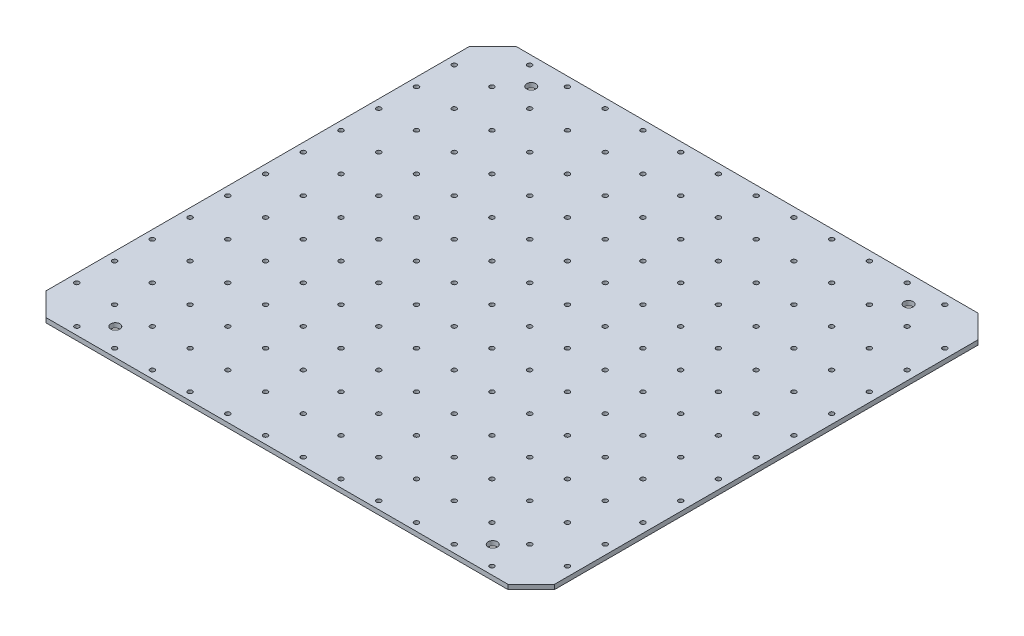
SolidWorks part; units mm, degrees
ref_plane "Front Plane" through (0, 0, 0) normal (0, 0, 1) x (1, 0, 0)
ref_plane "Top Plane" through (0, 0, 0) normal (0, 1, 0) x (1, 0, 0)
ref_plane "Right Plane" through (0, 0, 0) normal (1, 0, 0) x (0, 0, -1)
sketch "Sketch3" plane through (0, 0, 0) normal (0, 1, 0) x (1, 0, 0)
  line L0 (-289.1077, -12.0015) -> (-289.1077, 262.9985)
  line L1 (-289.1077, 262.9985) -> (-274.1077, 277.9985)
  line L2 (-274.1077, 277.9985) -> (25.8923, 277.9985)
  line L3 (25.8923, 277.9985) -> (40.8923, 262.9985)
  line L4 (40.8923, 262.9985) -> (40.8923, -12.0015)
  line L5 (40.8923, -12.0015) -> (25.8923, -27.0015)
  line L6 (25.8923, -27.0015) -> (-274.1077, -27.0015)
  line L7 (-274.1077, -27.0015) -> (-289.1077, -12.0015)
  line L8 (-274.1077, -31.4199) -> (-274.1077, 49968.5801) construction
  line L9 (25.8923, -27.0605) -> (25.8923, 49972.9395) construction
  line L10 (-289.1667, 262.9985) -> (49710.8333, 262.9985) construction
  dimension "D1" = 300
  dimension "D2" = 275
  dimension "D3" = 300
  dimension "D4" = 275
  dimension "D5" = 15
  dimension "D6" = 15
  dimension "D7" = 15
  dimension "D8" = 15
  dimension "D9" = 15
extrude "Boss-Extrude1" add sketch "Sketch3" along normal blind 3
hole_wizard "Ø3.0mm Dowel Slot3" positions "Sketch8" profile "Sketch9" size "Ø3.0" standard "ANSI Metric" slot yes
sketch "Sketch8" plane through (0, 3, 0) normal (0, 1, 0) x (1, 0, 0)
  line L0 (-274.1077, -27.0015) -> (25.8923, -27.0015) construction
  line L1 (-289.1077, 262.9985) -> (-289.1077, -12.0015) construction
  point P0 (-259.1077, -22.0015)
  point P11 (-234.6077, -22.0015)
  point P12 (-210.1077, -22.0015)
  point P13 (-185.6077, -22.0015)
  point P14 (-161.1077, -22.0015)
  point P15 (-136.6077, -22.0015)
  point P16 (-112.1077, -22.0015)
  point P17 (-87.6077, -22.0015)
  point P18 (-63.1077, -22.0015)
  point P19 (-38.6077, -22.0015)
  point P20 (-14.1077, -22.0015)
  point P21 (10.3923, -22.0015)
  point P30 (-259.1077, 2.4985)
  point P31 (-259.1077, 26.9985)
  point P32 (-259.1077, 51.4985)
  point P33 (-259.1077, 75.9985)
  point P34 (-259.1077, 100.4985)
  point P35 (-259.1077, 124.9985)
  point P36 (-259.1077, 149.4985)
  point P37 (-259.1077, 173.9985)
  point P38 (-259.1077, 198.4985)
  point P39 (-259.1077, 222.9985)
  point P40 (-259.1077, 247.4985)
  point P41 (-259.1077, 271.9985)
  point P60 (-234.6077, 2.4985)
  point P61 (-210.1077, 2.4985)
  point P62 (-185.6077, 2.4985)
  point P63 (-161.1077, 2.4985)
  point P64 (-136.6077, 2.4985)
  point P65 (-112.1077, 2.4985)
  point P66 (-87.6077, 2.4985)
  point P67 (-63.1077, 2.4985)
  point P68 (-38.6077, 2.4985)
  point P69 (-14.1077, 2.4985)
  point P70 (10.3923, 2.4985)
  point P71 (-234.6077, 26.9985)
  point P72 (-210.1077, 26.9985)
  point P73 (-185.6077, 26.9985)
  point P74 (-161.1077, 26.9985)
  point P75 (-136.6077, 26.9985)
  point P76 (-112.1077, 26.9985)
  point P77 (-87.6077, 26.9985)
  point P78 (-63.1077, 26.9985)
  point P79 (-38.6077, 26.9985)
  point P80 (-14.1077, 26.9985)
  point P81 (10.3923, 26.9985)
  point P82 (-234.6077, 51.4985)
  point P83 (-210.1077, 51.4985)
  point P84 (-185.6077, 51.4985)
  point P85 (-161.1077, 51.4985)
  point P86 (-136.6077, 51.4985)
  point P87 (-112.1077, 51.4985)
  point P88 (-87.6077, 51.4985)
  point P89 (-63.1077, 51.4985)
  point P90 (-38.6077, 51.4985)
  point P91 (-14.1077, 51.4985)
  point P92 (10.3923, 51.4985)
  point P93 (-234.6077, 75.9985)
  point P94 (-210.1077, 75.9985)
  point P95 (-185.6077, 75.9985)
  point P96 (-161.1077, 75.9985)
  point P97 (-136.6077, 75.9985)
  point P98 (-112.1077, 75.9985)
  point P99 (-87.6077, 75.9985)
  point P100 (-63.1077, 75.9985)
  point P101 (-38.6077, 75.9985)
  point P102 (-14.1077, 75.9985)
  point P103 (10.3923, 75.9985)
  point P104 (-234.6077, 100.4985)
  point P105 (-210.1077, 100.4985)
  point P106 (-185.6077, 100.4985)
  point P107 (-161.1077, 100.4985)
  point P108 (-136.6077, 100.4985)
  point P109 (-112.1077, 100.4985)
  point P110 (-87.6077, 100.4985)
  point P111 (-63.1077, 100.4985)
  point P112 (-38.6077, 100.4985)
  point P113 (-14.1077, 100.4985)
  point P114 (10.3923, 100.4985)
  point P115 (-234.6077, 124.9985)
  point P116 (-210.1077, 124.9985)
  point P117 (-185.6077, 124.9985)
  point P118 (-161.1077, 124.9985)
  point P119 (-136.6077, 124.9985)
  point P120 (-112.1077, 124.9985)
  point P121 (-87.6077, 124.9985)
  point P122 (-63.1077, 124.9985)
  point P123 (-38.6077, 124.9985)
  point P124 (-14.1077, 124.9985)
  point P125 (10.3923, 124.9985)
  point P126 (-234.6077, 149.4985)
  point P127 (-210.1077, 149.4985)
  point P128 (-185.6077, 149.4985)
  point P129 (-161.1077, 149.4985)
  point P130 (-136.6077, 149.4985)
  point P131 (-112.1077, 149.4985)
  point P132 (-87.6077, 149.4985)
  point P133 (-63.1077, 149.4985)
  point P134 (-38.6077, 149.4985)
  point P135 (-14.1077, 149.4985)
  point P136 (10.3923, 149.4985)
  point P137 (-234.6077, 173.9985)
  point P138 (-210.1077, 173.9985)
  point P139 (-185.6077, 173.9985)
  point P140 (-161.1077, 173.9985)
  point P141 (-136.6077, 173.9985)
  point P142 (-112.1077, 173.9985)
  point P143 (-87.6077, 173.9985)
  point P144 (-63.1077, 173.9985)
  point P145 (-38.6077, 173.9985)
  point P146 (-14.1077, 173.9985)
  point P147 (10.3923, 173.9985)
  point P148 (-234.6077, 198.4985)
  point P149 (-210.1077, 198.4985)
  point P150 (-185.6077, 198.4985)
  point P151 (-161.1077, 198.4985)
  point P152 (-136.6077, 198.4985)
  point P153 (-112.1077, 198.4985)
  point P154 (-87.6077, 198.4985)
  point P155 (-63.1077, 198.4985)
  point P156 (-38.6077, 198.4985)
  point P157 (-14.1077, 198.4985)
  point P158 (10.3923, 198.4985)
  point P159 (-234.6077, 222.9985)
  point P160 (-210.1077, 222.9985)
  point P161 (-185.6077, 222.9985)
  point P162 (-161.1077, 222.9985)
  point P163 (-136.6077, 222.9985)
  point P164 (-112.1077, 222.9985)
  point P165 (-87.6077, 222.9985)
  point P166 (-63.1077, 222.9985)
  point P167 (-38.6077, 222.9985)
  point P168 (-14.1077, 222.9985)
  point P169 (10.3923, 222.9985)
  point P170 (-234.6077, 247.4985)
  point P171 (-210.1077, 247.4985)
  point P172 (-185.6077, 247.4985)
  point P173 (-161.1077, 247.4985)
  point P174 (-136.6077, 247.4985)
  point P175 (-112.1077, 247.4985)
  point P176 (-87.6077, 247.4985)
  point P177 (-63.1077, 247.4985)
  point P178 (-38.6077, 247.4985)
  point P179 (-14.1077, 247.4985)
  point P180 (10.3923, 247.4985)
  point P181 (-234.6077, 271.9985)
  point P182 (-210.1077, 271.9985)
  point P183 (-185.6077, 271.9985)
  point P184 (-161.1077, 271.9985)
  point P185 (-136.6077, 271.9985)
  point P186 (-112.1077, 271.9985)
  point P187 (-87.6077, 271.9985)
  point P188 (-63.1077, 271.9985)
  point P189 (-38.6077, 271.9985)
  point P190 (-14.1077, 271.9985)
  point P191 (10.3923, 271.9985)
  point P224 (34.8923, 2.4985)
  point P225 (34.8923, 26.9985)
  point P226 (34.8923, 51.4985)
  point P227 (34.8923, 75.9985)
  point P228 (34.8923, 100.4985)
  point P229 (34.8923, 124.9985)
  point P230 (34.8923, 149.4985)
  point P231 (34.8923, 173.9985)
  point P232 (34.8923, 198.4985)
  point P233 (34.8923, 222.9985)
  point P234 (34.8923, 247.4985)
  point P254 (-283.6077, 2.4985)
  point P255 (-283.6077, 26.9985)
  point P256 (-283.6077, 51.4985)
  point P257 (-283.6077, 75.9985)
  point P258 (-283.6077, 100.4985)
  point P259 (-283.6077, 124.9985)
  point P260 (-283.6077, 149.4985)
  point P261 (-283.6077, 173.9985)
  point P262 (-283.6077, 198.4985)
  point P263 (-283.6077, 222.9985)
  point P264 (-283.6077, 247.4985)
  dimension "D1" = 5
  dimension "D2" = 30
  dimension "D6" = 2
  dimension "D3" = 12
  dimension "D4" = 13
  dimension "D5" = 13
  dimension "D7" = 2
sketch "Sketch9" plane through (-259.1077, 3, 22.0015) normal (1, 0, 0) x (0, 0, 1)
  line L0 (0, 0) -> (0, 6.1013)
  line L1 (0, 6.1013) -> (1.5, 5.2)
  line L2 (1.5, 5.2) -> (1.5, 0)
  line L5 (1.5, 0) -> (0, 0)
  line L10 (0, 6.1013) -> (-1.5, 5.2) construction
  line L11 (0, -6.35) -> (0, 107.95) construction
  dimension "Hole Dia." = 3
  dimension "Hole Depth" = 5.2
  dimension "Drill Angle" = 118
hole_wizard "Ø6.0mm Dowel Slot1" positions "Sketch10" profile "Sketch11" size "Ø6.0" standard "ANSI Metric" slot yes end condition through all
sketch "Sketch10" plane through (0, 3, 0) normal (0, 1, 0) x (1, 0, 0)
  line L0 (-274.1077, -27.0015) -> (25.8923, -27.0015) construction
  line L1 (40.8923, -12.0015) -> (40.8923, 262.9985) construction
  line L2 (25.8923, 277.9985) -> (-274.1077, 277.9985) construction
  line L3 (-289.1077, 262.9985) -> (-289.1077, -12.0015) construction
  point P0 (-1.6077, -9.5015)
  point P7 (-1.6077, 260.4985)
  point P12 (-246.6077, 260.4985)
  point P17 (-246.6077, -9.5015)
  dimension "D1" = 17.5
  dimension "D2" = 42.5
  dimension "D3" = 17.5
  dimension "D4" = 42.5
sketch "Sketch11" plane through (-1.6077, 3, 9.5015) normal (1, 0, 0) x (0, 0, 1)
  line L0 (0, 0) -> (0, 3)
  line L1 (0, 3) -> (3, 3)
  line L2 (3, 3) -> (3, 0)
  line L5 (3, 0) -> (0, 0)
  line L11 (0, -6.35) -> (0, 107.95) construction
  dimension "Thru Hole Dia." = 6
  dimension "Thru Hole Depth" = 3
